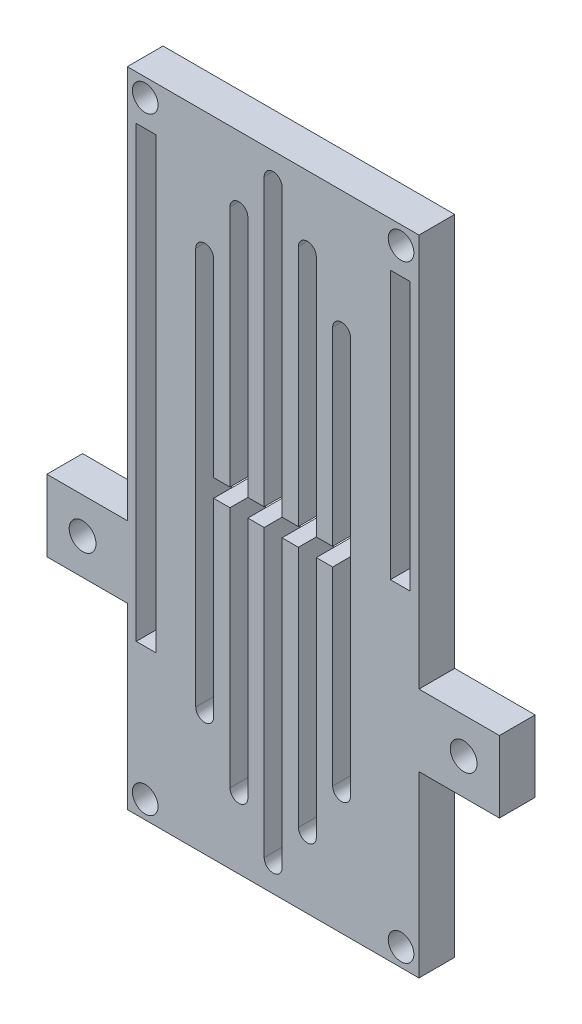
SolidWorks part; units mm, degrees
ref_plane "Alzado" through (0, 0, 0) normal (0, 0, 1) x (1, 0, 0)
ref_plane "Planta" through (0, 0, 0) normal (0, 1, 0) x (1, 0, 0)
ref_plane "Vista lateral" through (0, 0, 0) normal (1, 0, 0) x (0, 0, -1)
sketch "Croquis1" plane through (0, 0, 0) normal (0, 0, 1) x (1, 0, 0)
  line L0 (16.32, 72) -> (16.32, 0) construction
  line L1 (0, 0) -> (32.64, 0)
  line L2 (0, 0) -> (0, 72)
  line L3 (0, 72) -> (32.64, 72)
  line L4 (32.64, 0) -> (32.64, 72)
  line L5 (0, 0) -> (32.64, 72) construction
  line L6 (0, 72) -> (32.64, 0) construction
  line L7 (29.2, 2.01) -> (3.44, 2.01) construction
  line L8 (30.635, 68.555) -> (30.635, 3.445) construction
  line L9 (29.2, 69.99) -> (3.44, 69.99) construction
  line L10 (2.005, 68.555) -> (2.005, 3.445) construction
  line L11 (16.32, 3.01) -> (16.32, 68.99) construction
  line L12 (15.32, 3.01) -> (15.32, 35)
  line L13 (17.32, 3.01) -> (17.32, 35)
  line L14 (29.635, 36) -> (5.83, 36) construction
  line L15 (29.635, 35) -> (28.81, 35)
  line L16 (29.635, 37) -> (28.81, 37)
  line L17 (12.49, 7.8513) -> (12.49, 34) construction
  line L18 (11.49, 7.8513) -> (11.49, 34)
  line L19 (13.49, 7.8513) -> (13.49, 34)
  line L20 (8.66, 13.7725) -> (8.66, 34) construction
  line L21 (7.66, 13.7725) -> (7.66, 34)
  line L22 (9.66, 13.7725) -> (9.66, 34)
  line L23 (4.83, 23.0991) -> (4.83, 34) construction
  line L24 (3.83, 23.0991) -> (3.83, 34)
  line L25 (5.83, 23.0991) -> (5.83, 34)
  line L26 (20.15, 7.8513) -> (20.15, 34) construction
  line L27 (21.15, 7.8513) -> (21.15, 34)
  line L28 (19.15, 7.8513) -> (19.15, 34)
  line L29 (23.98, 13.7725) -> (23.98, 34) construction
  line L30 (24.98, 13.7725) -> (24.98, 34)
  line L31 (22.98, 13.7725) -> (22.98, 34)
  line L32 (27.81, 23.0991) -> (27.81, 34) construction
  line L33 (28.81, 23.0991) -> (28.81, 34)
  line L34 (26.81, 23.0991) -> (26.81, 34)
  line L35 (0, 36) -> (3.005, 36) construction
  line L36 (4.83, 48.9009) -> (4.83, 38) construction
  line L37 (3.83, 48.9009) -> (3.83, 38)
  line L38 (5.83, 48.9009) -> (5.83, 38)
  line L39 (8.66, 58.2275) -> (8.66, 38) construction
  line L40 (7.66, 58.2275) -> (7.66, 38)
  line L41 (9.66, 58.2275) -> (9.66, 38)
  line L42 (12.49, 64.1487) -> (12.49, 38) construction
  line L43 (11.49, 64.1487) -> (11.49, 38)
  line L44 (13.49, 64.1487) -> (13.49, 38)
  line L45 (20.15, 64.1487) -> (20.15, 38) construction
  line L46 (21.15, 64.1487) -> (21.15, 38)
  line L47 (19.15, 64.1487) -> (19.15, 38)
  line L48 (23.98, 58.2275) -> (23.98, 38) construction
  line L49 (24.98, 58.2275) -> (24.98, 38)
  line L50 (22.98, 58.2275) -> (22.98, 38)
  line L51 (27.81, 48.9009) -> (27.81, 38) construction
  line L52 (28.81, 48.9009) -> (28.81, 38)
  line L53 (26.81, 48.9009) -> (26.81, 38)
  line L54 (5.83, 38) -> (5.83, 37)
  line L55 (3.83, 38) -> (3.83, 37)
  line L56 (3.83, 37) -> (3.005, 37)
  line L57 (9.66, 34) -> (9.66, 35)
  line L58 (5.83, 36) -> (32.64, 36) construction
  line L59 (3.83, 35) -> (3.005, 35)
  line L60 (5.83, 35) -> (5.83, 34)
  line L61 (3.83, 35) -> (3.83, 34)
  line L62 (7.66, 38) -> (7.66, 37)
  line L63 (11.49, 38) -> (11.49, 37)
  line L64 (13.49, 38) -> (13.49, 37)
  line L65 (19.15, 38) -> (19.15, 37)
  line L66 (21.15, 38) -> (21.15, 37)
  line L67 (22.98, 38) -> (22.98, 37)
  line L68 (24.98, 38) -> (24.98, 37)
  line L69 (26.81, 38) -> (26.81, 37)
  line L70 (28.81, 38) -> (28.81, 37)
  line L71 (7.66, 35) -> (7.66, 34)
  line L72 (9.66, 37) -> (9.66, 38)
  line L73 (7.66, 35) -> (5.83, 35)
  line L74 (7.66, 37) -> (5.83, 37)
  line L75 (11.49, 35) -> (11.49, 34)
  line L76 (11.49, 37) -> (9.66, 37)
  line L77 (11.49, 35) -> (9.66, 35)
  line L78 (15.32, 37) -> (13.49, 37)
  line L79 (15.32, 37) -> (15.32, 68.99)
  line L80 (15.32, 35) -> (13.49, 35)
  line L81 (19.15, 35) -> (17.32, 35)
  line L82 (19.15, 37) -> (17.32, 37)
  line L83 (21.15, 35) -> (21.15, 34)
  line L84 (19.15, 35) -> (19.15, 34)
  line L85 (17.32, 37) -> (17.32, 68.99)
  line L86 (13.49, 35) -> (13.49, 34)
  line L87 (22.98, 35) -> (22.98, 34)
  line L88 (24.98, 35) -> (24.98, 34)
  line L89 (26.81, 35) -> (26.81, 34)
  line L90 (28.81, 35) -> (28.81, 34)
  line L91 (22.98, 35) -> (21.15, 35)
  line L92 (26.81, 35) -> (24.98, 35)
  line L93 (26.81, 37) -> (24.98, 37)
  line L94 (22.98, 37) -> (21.15, 37)
  circle A0 centre (2.005, 69.99) radius 1.435
  circle A1 centre (2.005, 2.01) radius 1.435
  circle A2 centre (30.635, 2.01) radius 1.435
  circle A3 centre (30.635, 69.99) radius 1.435
  arc A4 (15.32, 3.01) -> (17.32, 3.01) centre (16.32, 3.01) ccw
  arc A5 (17.32, 68.99) -> (15.32, 68.99) centre (16.32, 68.99) ccw
  arc A6 (29.635, 35) -> (29.635, 37) centre (29.635, 36) ccw
  arc A7 (3.005, 37) -> (3.005, 35) centre (3.005, 36) ccw
  arc A8 (16.32, 2.01) -> (16.32, 69.99) centre (49.516, 36) cw construction
  arc A9 (11.49, 7.8513) -> (13.49, 7.8513) centre (12.49, 7.8513) ccw
  arc A11 (7.66, 13.7725) -> (9.66, 13.7725) centre (8.66, 13.7725) ccw
  arc A13 (3.83, 23.0991) -> (5.83, 23.0991) centre (4.83, 23.0991) ccw
  arc A15 (21.15, 7.8513) -> (19.15, 7.8513) centre (20.15, 7.8513) cw
  arc A17 (24.98, 13.7725) -> (22.98, 13.7725) centre (23.98, 13.7725) cw
  arc A19 (28.81, 23.0991) -> (26.81, 23.0991) centre (27.81, 23.0991) cw
  arc A21 (3.83, 48.9009) -> (5.83, 48.9009) centre (4.83, 48.9009) cw
  arc A23 (7.66, 58.2275) -> (9.66, 58.2275) centre (8.66, 58.2275) cw
  arc A25 (11.49, 64.1487) -> (13.49, 64.1487) centre (12.49, 64.1487) cw
  arc A27 (21.15, 64.1487) -> (19.15, 64.1487) centre (20.15, 64.1487) ccw
  arc A29 (24.98, 58.2275) -> (22.98, 58.2275) centre (23.98, 58.2275) ccw
  arc A31 (28.81, 48.9009) -> (26.81, 48.9009) centre (27.81, 48.9009) ccw
  point P4 (16.32, 36)
  point P26 (16.32, 36)
  point P33 (16.32, 36)
  point P43 (12.49, 20.9257)
  point P48 (8.66, 23.8863)
  point P55 (4.83, 28.5495)
  point P64 (20.15, 20.9257)
  point P71 (23.98, 23.8863)
  point P78 (27.81, 28.5495)
  point P87 (4.83, 43.4505)
  point P94 (8.66, 48.1137)
  point P101 (12.49, 51.0743)
  point P108 (20.15, 51.0743)
  point P115 (23.98, 48.1137)
  point P122 (27.81, 43.4505)
  dimension "D3" = 2.87
  dimension "D7" = 2
  dimension "D9" = 2
  dimension "D1" = 72
  dimension "D2" = 32.64
  dimension "D4" = 2.005
  dimension "D5" = 2.01
  dimension "D6" = 2.01
  dimension "D8" = 2
  dimension "D10" = 1.83
  dimension "D11" = 2
  dimension "D13" = 2
  dimension "D15" = 1.83
  dimension "D16" = 1.83
extrude "Saliente-Extruir4" add sketch "Croquis1" along normal blind 4
sketch "Croquis3" plane through (0, 0, 4) normal (0, 0, 1) x (1, 0, 0)
  line L1 (-1, 20) -> (-9, 20)
  line L2 (-1, 20) -> (-1, 28) construction
  line L3 (-1, 28) -> (-9, 28)
  line L4 (-9, 20) -> (-9, 28)
  line L5 (-1, 20) -> (-9, 28) construction
  line L6 (-1, 28) -> (-9, 20) construction
  line L7 (0, -5) -> (32.64, -5) construction
  line L8 (0, 0) -> (32.64, 0) construction
  line L9 (16.32, -5) -> (16.32, 72) construction
  line L10 (32.64, 72) -> (0, 72) construction
  line L11 (33.64, 28) -> (41.64, 20) construction
  line L12 (33.64, 20) -> (41.64, 28) construction
  line L13 (41.64, 20) -> (41.64, 28)
  line L14 (33.64, 28) -> (41.64, 28)
  line L15 (33.64, 20) -> (33.64, 28) construction
  line L16 (33.64, 20) -> (41.64, 20)
  line L18 (0, 72) -> (0, 0) construction
  line L19 (-1, 28) -> (0, 28)
  line L20 (0, 28) -> (0, 20)
  line L21 (-9, 20) -> (-1, 20) construction
  line L22 (0, 20) -> (-1, 20)
  line L23 (33.64, 28) -> (32.64, 28)
  line L24 (32.64, 0) -> (32.64, 72) construction
  line L25 (32.64, 28) -> (32.64, 20)
  line L26 (32.64, 20) -> (33.64, 20)
  circle A0 centre (-5, 24) radius 2.85
  circle A1 centre (37.64, 24) radius 2.85
  circle A2 centre (-5, 24) radius 1.5
  circle A3 centre (37.64, 24) radius 1.5
  point P4 (-5, 24)
  point P21 (37.64, 24)
  dimension "D5" = 1
  dimension "D1" = 5
  dimension "D2" = 20
  dimension "D3" = 8
  dimension "D4" = 8
extrude "Saliente-Extruir5" add sketch "Croquis3" against normal up to surface (4 mm away) contours L4 L1 L2 L3 A0 | A0 A2 | L15 L16 L13 L14 A1 | A1 A3
sketch "Croquis5" plane through (0, 0, 4) normal (0, 0, 1) x (1, 0, 0)
  line L0 (32.64, 72) -> (0, 72) construction
  line L1 (1, 67) -> (3.2, 67)
  line L2 (1, 67) -> (1, 16.8)
  line L3 (1, 16.8) -> (3.2, 16.8)
  line L4 (3.2, 67) -> (3.2, 16.8)
  line L5 (1, 67) -> (3.2, 16.8) construction
  line L6 (1, 16.8) -> (3.2, 67) construction
  line L7 (0, 72) -> (0, 28) construction
  line L9 (32.64, 28) -> (32.64, 72) construction
  line L10 (29.44, 67) -> (31.64, 67)
  line L11 (29.44, 67) -> (29.44, 37)
  line L12 (29.44, 37) -> (31.64, 37)
  line L13 (31.64, 67) -> (31.64, 37)
  line L14 (29.44, 67) -> (31.64, 37) construction
  line L15 (29.44, 37) -> (31.64, 67) construction
  point P4 (2.1, 41.9)
  point P15 (30.54, 52)
  dimension "D1" = 2.2
  dimension "D2" = 50.2
  dimension "D3" = 5
  dimension "D4" = 1
  dimension "D5" = 1
  dimension "D6" = 5
  dimension "D7" = 30
  dimension "D8" = 2.2
sketch "Croquis6" plane through (0, 0, 4) normal (0, 0, 1) x (1, 0, 0)
  line L0 (7.66, 58.2275) -> (7.66, 37) construction
  line L1 (7.66, 51) -> (1.6917, 51)
  line L2 (7.66, 51) -> (7.66, 21)
  line L3 (7.66, 21) -> (1.6917, 21)
  line L4 (1.6917, 51) -> (1.6917, 21)
  line L5 (7.66, 51) -> (1.6917, 21) construction
  line L6 (7.66, 21) -> (1.6917, 51) construction
  line L7 (5.83, 35) -> (7.66, 35) construction
  line L8 (16.32, 72) -> (16.32, 0) construction
  line L9 (32.64, 72) -> (0, 72) construction
  line L10 (0, 0) -> (32.64, 0) construction
  line L11 (30.9483, 51) -> (30.9483, 21)
  line L12 (24.98, 21) -> (30.9483, 21)
  line L13 (24.98, 51) -> (24.98, 21)
  line L14 (24.98, 51) -> (30.9483, 51)
  point P4 (4.6759, 36)
  dimension "D1" = 5.9683
  dimension "D2" = 30
  dimension "D3" = 14
extrude "Saliente-Extruir6" add sketch "Croquis6" against normal up to surface (4 mm away) up to face at (29.2, 2.01, 0)
extrude "Cortar-Extruir1" cut sketch "Croquis5" against normal up to surface (4 mm away) up to face at (16.32, 36, 0)
